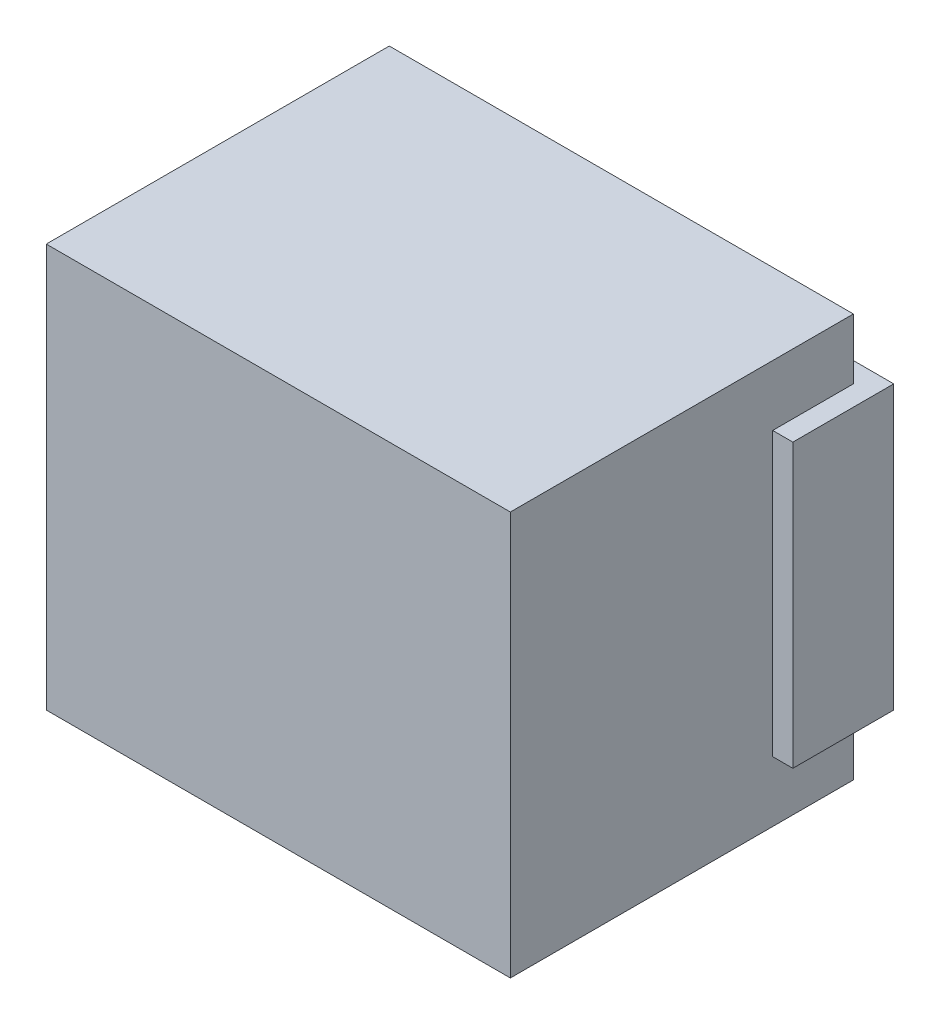
SolidWorks part; units mm, degrees
ref_plane "Front Plane" through (0, 0, 0) normal (0, 0, 1) x (1, 0, 0)
ref_plane "Top Plane" through (0, 0, 0) normal (0, 1, 0) x (1, 0, 0)
ref_plane "Right Plane" through (0, 0, 0) normal (1, 0, 0) x (0, 0, -1)
sketch "Sketch1" plane through (0, 0, 0) normal (0, 1, 0) x (1, 0, 0)
  line L0 (-1.15, -0.1) -> (-1.15, -1.8)
  line L1 (-1.15, -1.8) -> (1.15, -1.8)
  line L2 (1.15, -1.8) -> (1.15, -0.1)
  line L7 (1.15, -0.1) -> (-1.15, -0.1)
  line L9 (0, -1.8) -> (0, 0) construction
  line L10 (-55, 0) -> (55, 0) construction
  dimension "D1" = 0.1
  dimension "D3" = 2.3
  dimension "D4" = 1.8
extrude "Boss-Extrude1" add sketch "Sketch1" along normal mid plane 2
sketch "Sketch2" plane through (0, 0, 0) normal (0, 1, 0) x (1, 0, 0)
  line L0 (0, -1.8) -> (0, -0.1) construction
  line L1 (-1.15, -1.8) -> (1.15, -1.8) construction
  line L2 (1.15, -0.1) -> (-1.15, -0.1) construction
  line L3 (-1.15, -0.5) -> (-1.25, -0.5)
  line L4 (-1.25, -0.5) -> (-1.25, 0)
  line L5 (-1.25, 0) -> (-0.85, 0)
  line L6 (-0.85, 0) -> (-0.85, -0.1)
  line L7 (-0.85, -0.1) -> (-1.15, -0.1)
  line L8 (-1.1, 0) -> (1.1, 0) construction
  line L9 (-1.15, -0.1) -> (-1.15, -0.5)
  line L10 (-1.15, -0.1) -> (-1.15, -1.8) construction
  line L11 (1.15, -0.1) -> (1.15, -0.5)
  line L17 (0.85, -0.1) -> (1.15, -0.1)
  line L18 (0.85, 0) -> (0.85, -0.1)
  line L19 (1.25, 0) -> (0.85, 0)
  line L20 (1.25, -0.5) -> (1.25, 0)
  line L21 (1.15, -0.5) -> (1.25, -0.5)
  line L22 (1.15, -1.8) -> (1.15, -0.1) construction
  dimension "D1" = 0.5
  dimension "D2" = 0.4
  dimension "D3" = 0.1
extrude "Boss-Extrude2" add sketch "Sketch2" along normal mid plane 1.4
